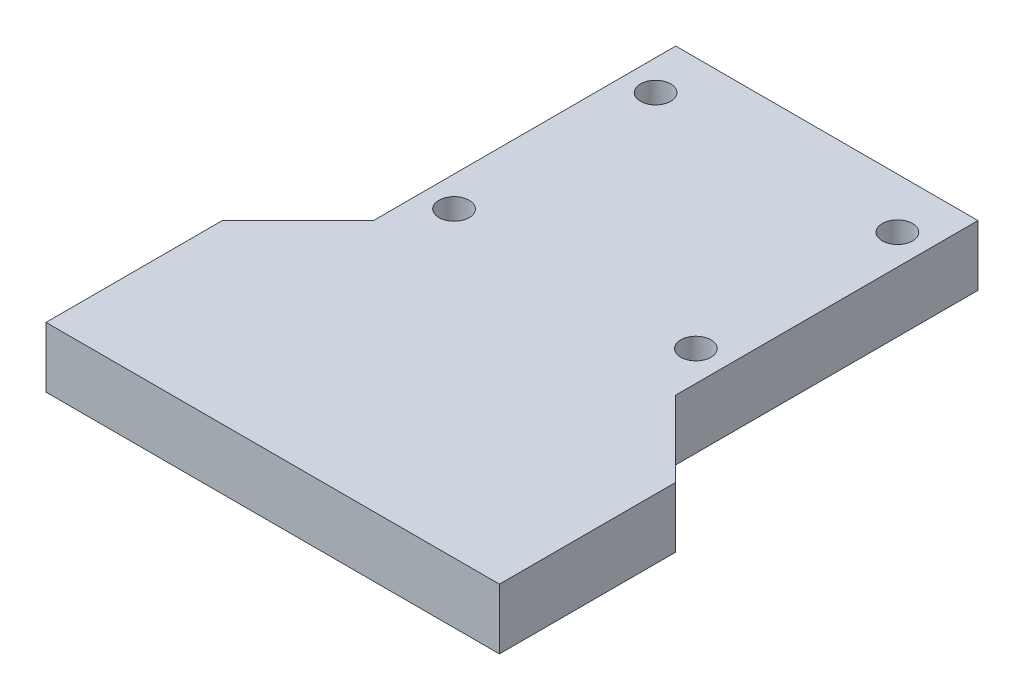
SolidWorks part; units mm, degrees
material "Beech"
ref_plane "Front Plane" through (0, 0, 0) normal (0, 0, 1) x (1, 0, 0)
ref_plane "Top Plane" through (0, 0, 0) normal (0, 1, 0) x (1, 0, 0)
ref_plane "Right Plane" through (0, 0, 0) normal (1, 0, 0) x (0, 0, -1)
sketch "Sketch1" plane through (0, 0, 0) normal (0, 1, 0) x (1, 0, 0)
  line L0 (-30, -30) -> (-45, -45)
  line L1 (-30, 30) -> (30, 30)
  line L2 (-30, 30) -> (-30, -30)
  line L4 (30, 30) -> (30, -30)
  line L5 (-30, 30) -> (30, -30) construction
  line L6 (-30, -30) -> (30, 30) construction
  line L7 (-45, -45) -> (-45, -80)
  line L8 (-45, -80) -> (45, -80)
  line L9 (45, -80) -> (45, -45)
  line L10 (45, -45) -> (30, -30)
  point P0 (0, 0)
  dimension "D1" = 60
  dimension "D2" = 60
  dimension "D3" = 90
extrude "Boss-Extrude1" add sketch "Sketch1" along normal blind 12
sketch "Sketch2" plane through (0, 12, 0) normal (0, 1, 0) x (1, 0, 0)
  line L0 (-24, 36.933) -> (-24, -38.3163) construction
  line L1 (24, 34.8909) -> (24, -38.3163) construction
  line L2 (-30, 30) -> (-30, -30) construction
  line L3 (30, -30) -> (30, 30) construction
  line L4 (30, 30) -> (-30, 30) construction
  circle A0 centre (-24, 20) radius 3
  circle A1 centre (-24, -20) radius 3
  circle A2 centre (24, 20) radius 3
  circle A3 centre (24, -20) radius 3
  dimension "D3" = 6
  dimension "D4" = 6
  dimension "D5" = 6
  dimension "D6" = 6
  dimension "D7" = 10
  dimension "D8" = 10
  dimension "D9" = 10
  dimension "D10" = 10
  dimension "D1" = 6
  dimension "D2" = 6
extrude "Cut-Extrude1" cut sketch "Sketch2" against normal up to next
